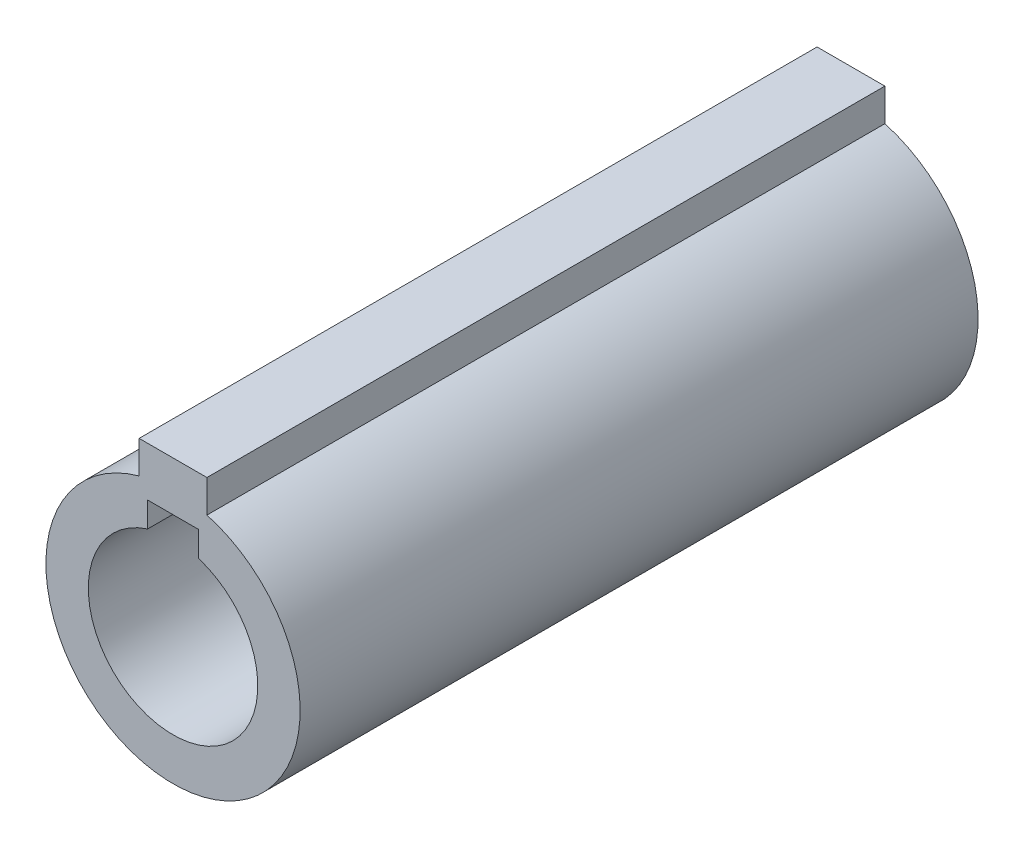
SolidWorks part; units mm, degrees
ref_plane "前视基准面" through (0, 0, 0) normal (0, 0, 1) x (1, 0, 0)
ref_plane "上视基准面" through (0, 0, 0) normal (0, 1, 0) x (1, 0, 0)
ref_plane "右视基准面" through (0, 0, 0) normal (1, 0, 0) x (0, 0, -1)
sketch "草图1" plane through (0, 0, 0) normal (0, 0, 1) x (1, 0, 0)
  line L0 (0, 21.2005) -> (0, -21.1644) construction
  line L1 (-19.1595, 0) -> (26.6272, 0) construction
  line L2 (-3, 9.5394) -> (-3, 12.5)
  line L3 (-3, 12.5) -> (3, 12.5)
  line L4 (3, 12.5) -> (3, 9.5394)
  line L5 (-4, 18.3) -> (-4, 14.4568)
  line L6 (-4, 18.3) -> (4, 18.3)
  line L7 (4, 18.3) -> (4, 14.4568)
  arc A0 (-3, 9.5394) -> (3, 9.5394) centre (0, 0) ccw
  arc A1 (-4, 14.4568) -> (4, 14.4568) centre (0, 0) ccw
  dimension "D1" = 20
  dimension "D2" = 30
  dimension "D3" = 6
  dimension "D4" = 3
  dimension "D5" = 12.5
  dimension "D6" = 8
  dimension "D7" = 4
  dimension "D8" = 18.3
extrude "凸台-拉伸1" add sketch "草图1" along normal blind 80
